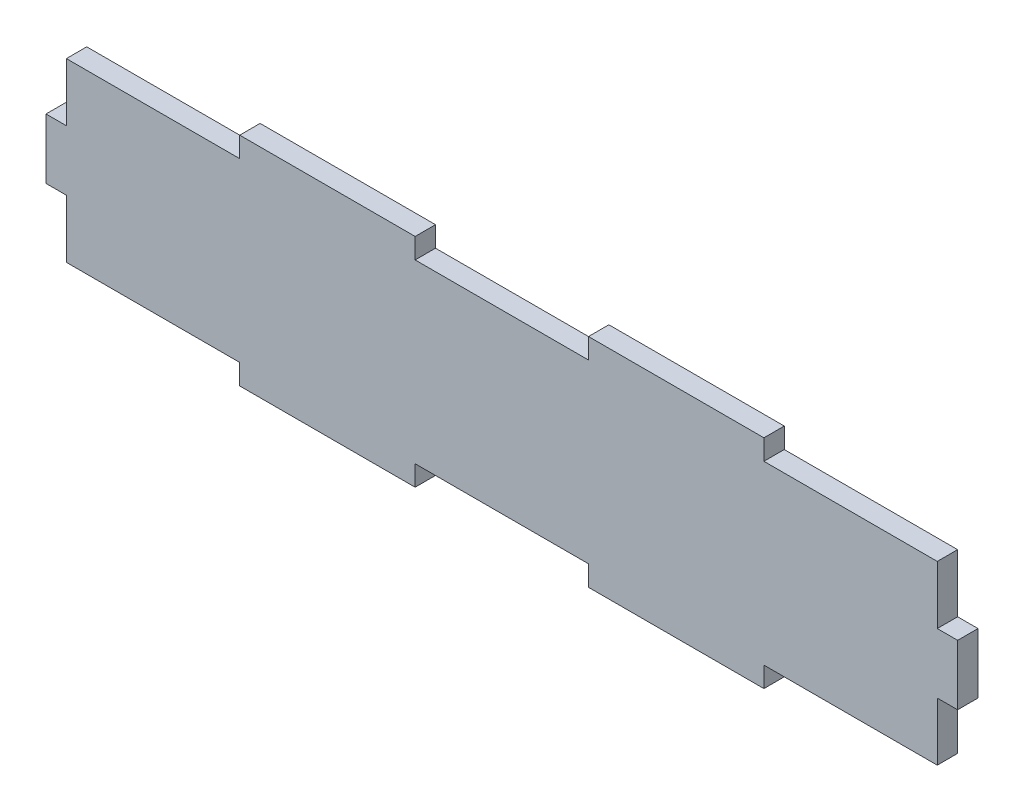
SolidWorks part; units mm, degrees
ref_plane "Front Plane" through (0, 0, 0) normal (0, 0, 1) x (1, 0, 0)
ref_plane "Top Plane" through (0, 0, 0) normal (0, 1, 0) x (1, 0, 0)
ref_plane "Right Plane" through (0, 0, 0) normal (1, 0, 0) x (0, 0, -1)
sketch "Sketch1" plane through (0, 0, 0) normal (0, 0, 1) x (1, 0, 0)
  line L0 (-64.15, -4.4333) -> (-67.15, -4.4333)
  line L1 (-67.15, -4.4333) -> (-67.15, 4.4333)
  line L2 (-67.15, 4.4333) -> (-64.15, 4.4333)
  line L3 (-64.15, 4.4333) -> (-64.15, 13)
  line L4 (-64.15, 13) -> (-38.61, 13)
  line L5 (-38.61, 13) -> (-38.61, 16)
  line L6 (-38.61, 16) -> (-12.77, 16)
  line L7 (-12.77, 16) -> (-12.77, 13)
  line L8 (-12.77, 13) -> (12.77, 13)
  line L9 (12.77, 13) -> (12.77, 16)
  line L10 (12.77, 16) -> (38.61, 16)
  line L11 (38.61, 16) -> (38.61, 13)
  line L12 (38.61, 13) -> (64.15, 13)
  line L13 (64.15, 13) -> (64.15, 4.4333)
  line L14 (64.15, 4.4333) -> (67.15, 4.4333)
  line L15 (67.15, 4.4333) -> (67.15, -4.4333)
  line L16 (67.15, -4.4333) -> (64.15, -4.4333)
  line L17 (-22.4406, 0) -> (15.5078, 0) construction
  line L18 (64.15, -13) -> (64.15, -4.4333)
  line L19 (38.61, -13) -> (64.15, -13)
  line L20 (38.61, -16) -> (38.61, -13)
  line L21 (12.77, -16) -> (38.61, -16)
  line L22 (12.77, -13) -> (12.77, -16)
  line L23 (-12.77, -13) -> (12.77, -13)
  line L24 (-12.77, -16) -> (-12.77, -13)
  line L25 (-38.61, -16) -> (-12.77, -16)
  line L26 (-38.61, -13) -> (-38.61, -16)
  line L27 (-64.15, -13) -> (-38.61, -13)
  line L28 (-64.15, -4.4333) -> (-64.15, -13)
  line L29 (-64.15, -4.4333) -> (-64.15, 4.1333) construction
  line L30 (-64.15, 4.1333) -> (-64.15, 4.4333) construction
  line L31 (-38.61, 13) -> (-13.07, 13) construction
  line L32 (-13.07, 13) -> (-12.77, 13) construction
  point P20 (-67.15, 0)
  point P31 (0, 0)
  point P34 (0, 13)
  point P36 (0, 0)
  dimension "D1" = 0.3
  dimension "D2" = 134.3
  dimension "D3" = 3
  dimension "D4" = 26
extrude "Boss-Extrude1" add sketch "Sketch1" along normal blind 3
